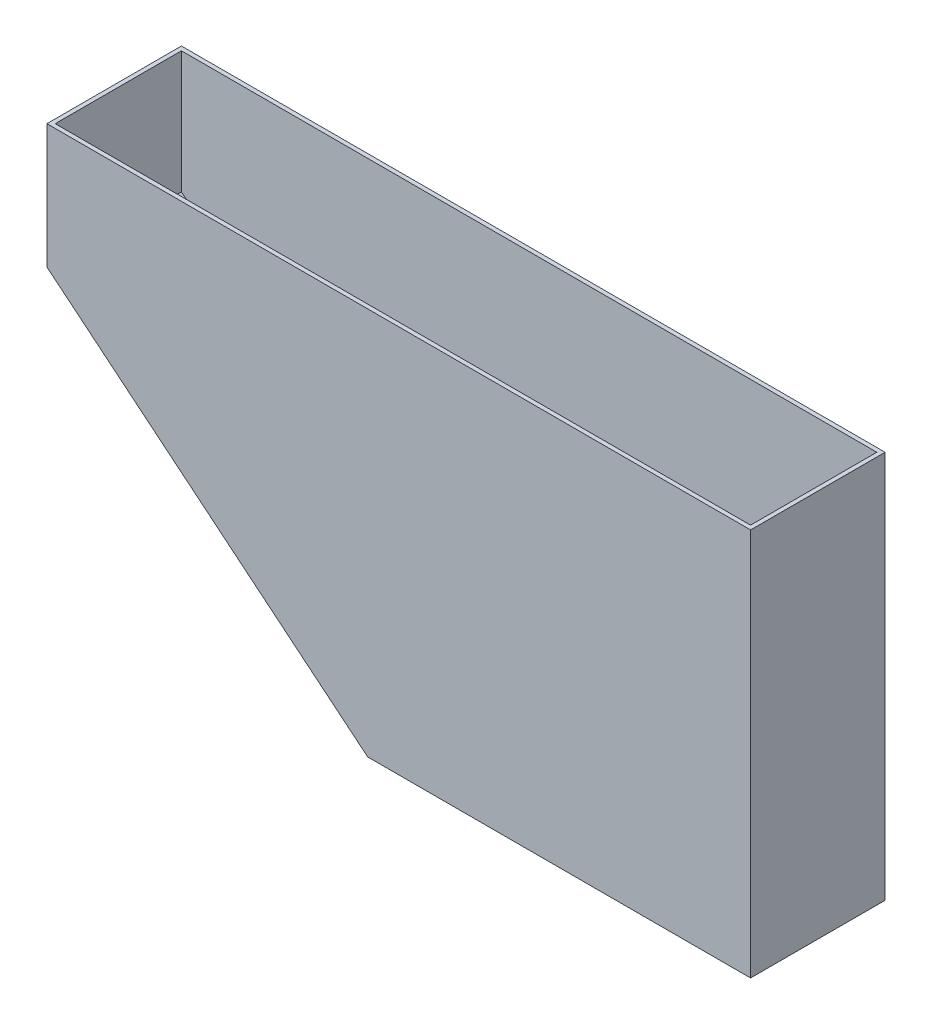
SolidWorks part; units mm, degrees
ref_plane "Front Plane" through (0, 0, 0) normal (0, 0, 1) x (1, 0, 0)
ref_plane "Top Plane" through (0, 0, 0) normal (0, 1, 0) x (1, 0, 0)
ref_plane "Right Plane" through (0, 0, 0) normal (1, 0, 0) x (0, 0, -1)
sketch "Sketch1" plane through (0, 0, 0) normal (0, 0, 1) x (1, 0, 0)
  line L0 (-304.0732, 21.5864) -> (5.9268, -233.4136)
  line L1 (-304.0732, 141.5864) -> (375.9268, 141.5864)
  line L2 (-304.0732, 141.5864) -> (-304.0732, 21.5864)
  line L3 (5.9268, -233.4136) -> (375.9268, -233.4136)
  line L4 (375.9268, 141.5864) -> (375.9268, -233.4136)
  dimension "D1" = 680
  dimension "D2" = 375
  dimension "D3" = 120
  dimension "D4" = 370
extrude "Boss-Extrude1" add sketch "Sketch1" along normal blind 130
shell "Shell1" thickness 4
